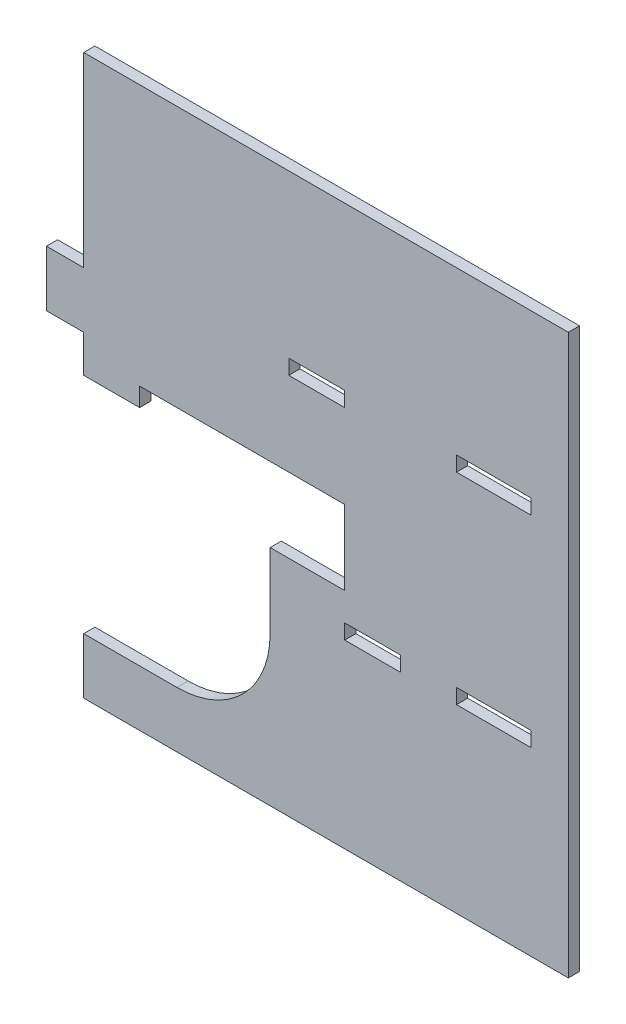
SolidWorks part; units mm, degrees
material "PBT General Purpose"
ref_plane "Front Plane" through (0, 0, 0) normal (0, 0, 1) x (1, 0, 0)
ref_plane "Top Plane" through (0, 0, 0) normal (0, 1, 0) x (1, 0, 0)
ref_plane "Right Plane" through (0, 0, 0) normal (1, 0, 0) x (0, 0, -1)
sketch "Sketch1" plane through (0, 0, 0) normal (0, 0, 1) x (1, 0, 0)
  line L1 (0, 0) -> (-10, 0)
  line L2 (0, 0) -> (0, 15) construction
  line L5 (-8.5, 8) -> (-3, 8)
  line L6 (-8.5, 8) -> (-8.5, 7.5)
  line L7 (-8.5, 7.5) -> (-10, 7.5)
  line L8 (-10, 7.5) -> (-10, 8.5)
  line L9 (-10, 8.5) -> (-11, 8.5)
  line L10 (-11, 8.5) -> (-11, 10)
  line L11 (-11, 10) -> (-10, 10)
  line L12 (-10, 10) -> (-10, 15)
  line L14 (-5, 1.5) -> (-10, 1.5)
  line L16 (-5, 1.5) -> (-5, 6)
  line L21 (-5, 6) -> (-3, 6)
  line L25 (-3, 8) -> (-3, 6)
  line L26 (-10, 15) -> (0, 15)
  line L30 (0, 0) -> (3, 0)
  line L31 (3, 0) -> (3, 15)
  line L32 (3, 15) -> (0, 15)
  line L34 (-10, 1.5) -> (-10, 0)
  dimension "D2" = 10
  dimension "D3" = 2
  dimension "D4" = 1.5
  dimension "D5" = 1
  dimension "D6" = 1
  dimension "D7" = 15
  dimension "D8" = 5
  dimension "D9" = 1.5
  dimension "D10" = 1.5
  dimension "D11" = 0.5
  dimension "D12" = 1
  dimension "D13" = 6
  dimension "D16" = 6
  dimension "D17" = 3
  dimension "D19" = 3
extrude "Boss-Extrude1" add sketch "Sketch1" along normal mid plane 0.3
fillet "Fillet4" radius 2.5 1 edges at (-5, 1.5, 0)
sketch "Sketch3" plane through (0, 0, 0.15) normal (0, 0, 1) x (1, 0, 0)
  line L0 (2, 5.25) -> (2, 10.25) construction
  line L1 (2, 5.25) -> (0, 5.25)
  line L2 (2, 5.25) -> (2, 4.85)
  line L3 (2, 4.85) -> (0, 4.85)
  line L4 (0, 5.25) -> (0, 4.85)
  line L5 (-1.5, 5.25) -> (-3, 5.25)
  line L6 (-1.5, 5.25) -> (-1.5, 4.85)
  line L7 (-1.5, 4.85) -> (-3, 4.85)
  line L8 (-3, 5.25) -> (-3, 4.85)
  line L9 (2, 10.65) -> (0, 10.65)
  line L10 (2, 10.65) -> (2, 10.25)
  line L11 (2, 10.25) -> (0, 10.25)
  line L12 (0, 10.65) -> (0, 10.25)
  line L13 (-3, 10.65) -> (-4.5, 10.65)
  line L14 (-3, 10.65) -> (-3, 10.25)
  line L15 (-3, 10.25) -> (-4.5, 10.25)
  line L16 (-4.5, 10.65) -> (-4.5, 10.25)
  line L18 (-11, 8.5) -> (-11, 10) construction
  line L19 (3, 0) -> (3, 15) construction
  point P18 (2, 7.75)
  point P21 (-11, 9.25)
  dimension "D1" = 0.4
  dimension "D2" = 0.4
  dimension "D3" = 2
  dimension "D4" = 1.5
  dimension "D5" = 1.5
  dimension "D6" = 5
  dimension "D7" = 1.5
  dimension "D8" = 1
  dimension "D9" = 1.5
  dimension "D10" = 3
extrude "Cut-Extrude1" cut sketch "Sketch3" against normal through all
equation "\"t\"= 0.3'thickness of the sheets"
equation "\"FlexJoint\"= 0.15'Width of flextures"
equation "\"FoldJoint\"= 0.4'Width of folding joints"
equation "\"AssembleAngle\"= 90'Angle of assembly parts"
equation "\"D1@Boss-Extrude1\"=\"t\""
